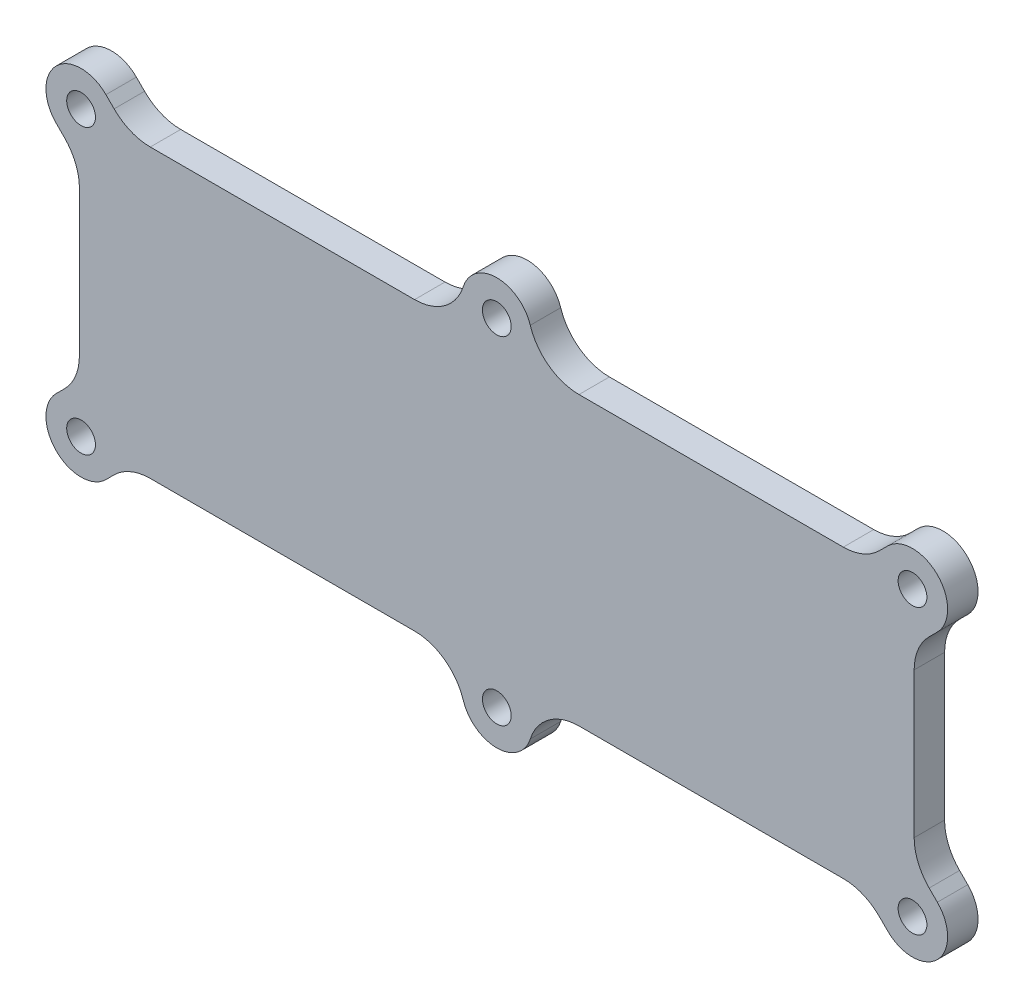
SolidWorks part; units mm, degrees
material "Custom Plastic"
ref_plane "X-Y Datum" through (0, 0, 0) normal (0, 0, 1) x (1, 0, 0)
ref_plane "X-Z Datum" through (0, 0, 0) normal (0, 1, 0) x (1, 0, 0)
ref_plane "Y-Z Datum" through (0, 0, 0) normal (1, 0, 0) x (0, 0, -1)
sketch "Sketch1" plane through (0, 0, 0) normal (0, 0, 1) x (1, 0, 0)
  line L14 (61.1737, 26.0894) -> (59.89, 24.8056)
  line L15 (54.2331, 22.4625) -> (12.8654, 22.4625)
  line L16 (-12.8654, 22.4625) -> (-54.2331, 22.4625)
  line L17 (-59.89, 24.8056) -> (-61.1737, 26.0894)
  line L18 (-68.9519, 18.3112) -> (-67.6681, 17.0275)
  line L19 (-65.325, 11.3706) -> (-65.325, -11.3706)
  line L20 (-67.6681, -17.0275) -> (-68.9519, -18.3112)
  line L21 (-61.1737, -26.0894) -> (-59.89, -24.8056)
  line L22 (-54.2331, -22.4625) -> (-12.8654, -22.4625)
  line L23 (12.8654, -22.4625) -> (54.2331, -22.4625)
  line L24 (59.89, -24.8056) -> (61.1737, -26.0894)
  line L25 (68.9519, -18.3112) -> (67.6681, -17.0275)
  line L26 (65.325, -11.3706) -> (65.325, 11.3706)
  line L27 (67.6681, 17.0275) -> (68.9519, 18.3112)
  line L28 (61.1737, 26.0894) -> (59.89, 24.8056)
  line L29 (54.2331, 22.4625) -> (12.8654, 22.4625)
  line L30 (-12.8654, 22.4625) -> (-54.2331, 22.4625)
  line L31 (-59.89, 24.8056) -> (-61.1737, 26.0894)
  line L32 (-68.9519, 18.3112) -> (-67.6681, 17.0275)
  line L33 (-65.325, 11.3706) -> (-65.325, -11.3706)
  line L34 (-67.6681, -17.0275) -> (-68.9519, -18.3112)
  line L35 (-61.1737, -26.0894) -> (-59.89, -24.8056)
  line L36 (-54.2331, -22.4625) -> (-12.8654, -22.4625)
  line L37 (12.8654, -22.4625) -> (54.2331, -22.4625)
  line L38 (59.89, -24.8056) -> (61.1737, -26.0894)
  line L39 (68.9519, -18.3112) -> (67.6681, -17.0275)
  line L40 (65.325, -11.3706) -> (65.325, 11.3706)
  line L41 (67.6681, 17.0275) -> (68.9519, 18.3112)
  arc A18 (54.2331, 22.4625) -> (59.89, 24.8056) centre (54.2331, 30.4625) ccw
  arc A19 (5.2415, 28.0386) -> (12.8654, 22.4625) centre (12.8654, 30.4625) ccw
  arc A20 (5.2415, 28.0386) -> (-5.2415, 28.0386) centre (0, 26.3722) ccw
  arc A21 (-12.8654, 22.4625) -> (-5.2415, 28.0386) centre (-12.8654, 30.4625) ccw
  arc A22 (-59.89, 24.8056) -> (-54.2331, 22.4625) centre (-54.2331, 30.4625) ccw
  arc A23 (-61.1737, 26.0894) -> (-68.9519, 18.3112) centre (-65.0628, 22.2003) ccw
  arc A24 (-65.325, 11.3706) -> (-67.6681, 17.0275) centre (-73.325, 11.3706) ccw
  arc A25 (-67.6681, -17.0275) -> (-65.325, -11.3706) centre (-73.325, -11.3706) ccw
  arc A26 (-68.9519, -18.3112) -> (-61.1737, -26.0894) centre (-65.0628, -22.2003) ccw
  arc A27 (-54.2331, -22.4625) -> (-59.89, -24.8056) centre (-54.2331, -30.4625) ccw
  arc A28 (-5.2415, -28.0386) -> (-12.8654, -22.4625) centre (-12.8654, -30.4625) ccw
  arc A29 (-5.2415, -28.0386) -> (5.2415, -28.0386) centre (0, -26.3722) ccw
  arc A30 (12.8654, -22.4625) -> (5.2415, -28.0386) centre (12.8654, -30.4625) ccw
  arc A31 (59.89, -24.8056) -> (54.2331, -22.4625) centre (54.2331, -30.4625) ccw
  arc A32 (61.1737, -26.0894) -> (68.9519, -18.3112) centre (65.0628, -22.2003) ccw
  arc A33 (65.325, -11.3706) -> (67.6681, -17.0275) centre (73.325, -11.3706) ccw
  arc A34 (67.6681, 17.0275) -> (65.325, 11.3706) centre (73.325, 11.3706) ccw
  arc A35 (68.9519, 18.3112) -> (61.1737, 26.0894) centre (65.0628, 22.2003) ccw
  arc A36 (54.2331, 22.4625) -> (59.89, 24.8056) centre (54.2331, 30.4625) ccw
  arc A37 (5.2415, 28.0386) -> (12.8654, 22.4625) centre (12.8654, 30.4625) ccw
  arc A38 (5.2415, 28.0386) -> (-5.2415, 28.0386) centre (0, 26.3722) ccw
  arc A39 (-12.8654, 22.4625) -> (-5.2415, 28.0386) centre (-12.8654, 30.4625) ccw
  arc A40 (-59.89, 24.8056) -> (-54.2331, 22.4625) centre (-54.2331, 30.4625) ccw
  arc A41 (-61.1737, 26.0894) -> (-68.9519, 18.3112) centre (-65.0628, 22.2003) ccw
  arc A42 (-65.325, 11.3706) -> (-67.6681, 17.0275) centre (-73.325, 11.3706) ccw
  arc A43 (-67.6681, -17.0275) -> (-65.325, -11.3706) centre (-73.325, -11.3706) ccw
  arc A44 (-68.9519, -18.3112) -> (-61.1737, -26.0894) centre (-65.0628, -22.2003) ccw
  arc A45 (-54.2331, -22.4625) -> (-59.89, -24.8056) centre (-54.2331, -30.4625) ccw
  arc A46 (-5.2415, -28.0386) -> (-12.8654, -22.4625) centre (-12.8654, -30.4625) ccw
  arc A47 (-5.2415, -28.0386) -> (5.2415, -28.0386) centre (0, -26.3722) ccw
  arc A48 (12.8654, -22.4625) -> (5.2415, -28.0386) centre (12.8654, -30.4625) ccw
  arc A49 (59.89, -24.8056) -> (54.2331, -22.4625) centre (54.2331, -30.4625) ccw
  arc A50 (61.1737, -26.0894) -> (68.9519, -18.3112) centre (65.0628, -22.2003) ccw
  arc A51 (65.325, -11.3706) -> (67.6681, -17.0275) centre (73.325, -11.3706) ccw
  arc A52 (67.6681, 17.0275) -> (65.325, 11.3706) centre (73.325, 11.3706) ccw
  arc A53 (68.9519, 18.3112) -> (61.1737, 26.0894) centre (65.0628, 22.2003) ccw
  dimension "D1" = 0
extrude "Boss-Extrude1" add sketch "Sketch1" along normal blind 4.7625
sketch "Sketch2" plane through (0, 0, 4.7625) normal (0, 0, 1) x (1, 0, 0)
  point P0 (-65.0628, 22.2003)
  point P1 (0, 26.3722)
  point P3 (65.0628, 22.2003)
  point P5 (65.0628, -22.2003)
  point P7 (0, -26.3722)
  point P9 (-65.0628, -22.2003)
hole_wizard "M4 Clearance Hole1" positions "Sketch2" profile "Sketch3" hole size "M4" standard "ANSI Metric" end condition through all
sketch "Sketch3" plane through (-65.0628, 22.2003, 4.7625) normal (1, 0, 0) x (0, -1, 0)
  line L0 (0, 0) -> (0, 4.7625)
  line L1 (0, 4.7625) -> (2.25, 4.7625)
  line L2 (2.25, 4.7625) -> (2.25, 0)
  line L5 (2.25, 0) -> (0, 0)
  line L11 (0, -6.35) -> (0, 107.95) construction
  dimension "Thru Hole Dia." = 4.5
  dimension "Thru Hole Depth" = 4.7625
